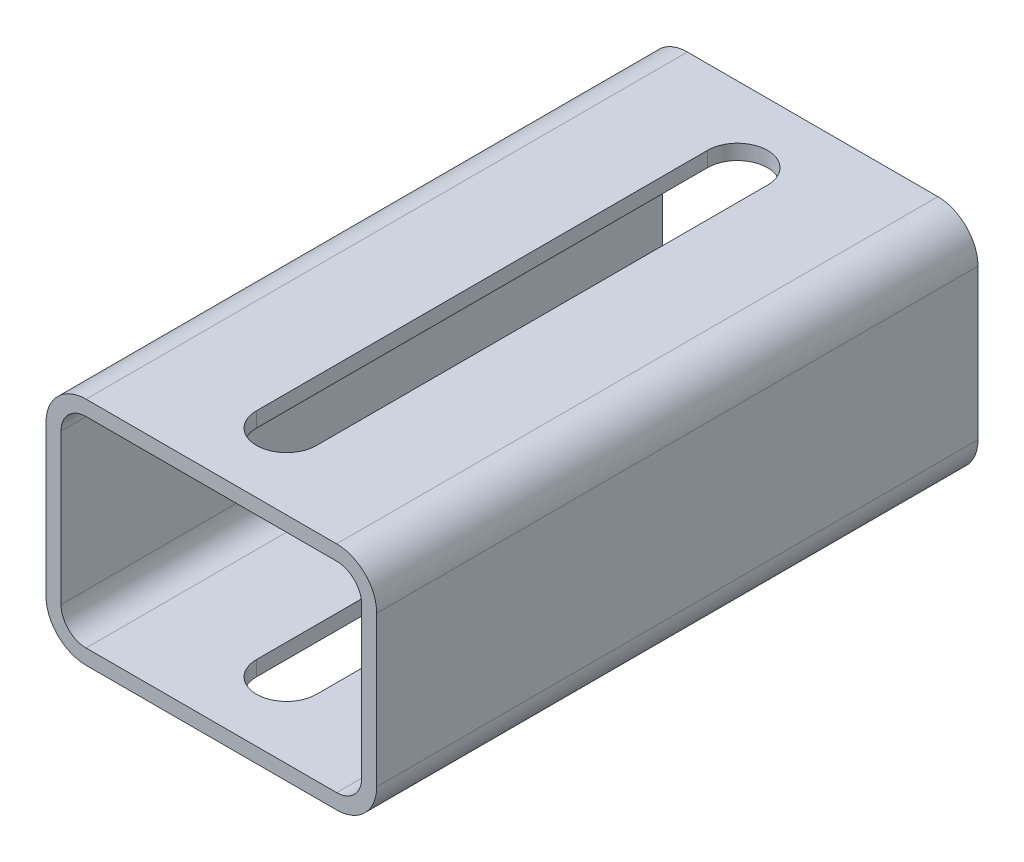
SolidWorks part; units mm, degrees
ref_plane "Front Plane" through (0, 0, 0) normal (0, 0, 1) x (1, 0, 0)
ref_plane "Top Plane" through (0, 0, 0) normal (0, 1, 0) x (1, 0, 0)
ref_plane "Right Plane" through (0, 0, 0) normal (1, 0, 0) x (0, 0, -1)
sketch "Sketch2" plane through (0, 0, 0) normal (0, 0, 1) x (1, 0, 0)
  line L1 (-25, 20) -> (25, 20)
  line L2 (-30, 15) -> (-30, -15)
  line L3 (-25, -20) -> (25, -20)
  line L4 (30, 15) -> (30, -15)
  line L5 (-30, 20) -> (30, -20) construction
  line L6 (-30, -20) -> (30, 20) construction
  arc A0 (-25, 20) -> (-30, 15) centre (-25, 15) ccw
  arc A1 (-30, -15) -> (-25, -20) centre (-25, -15) ccw
  arc A2 (25, -20) -> (30, -15) centre (25, -15) ccw
  arc A3 (25, 20) -> (30, 15) centre (25, 15) cw
  point P0 (0, 0)
  dimension "D3" = 5
  dimension "D1" = 60
  dimension "D2" = 40
extrude "Extrude-Thin1" add sketch "Sketch2" along normal mid plane 120 thin thin type one direction wall 3
sketch "Sketch4" plane through (0, 23, 0) normal (0, 1, 0) x (1, 0, 0)
  line L0 (0, 45) -> (0, -45) construction
  line L1 (6, 45) -> (6, -45)
  line L2 (-6, 45) -> (-6, -45)
  arc A0 (6, 45) -> (-6, 45) centre (0, 45) ccw
  arc A1 (-6, -45) -> (6, -45) centre (0, -45) ccw
  point P2 (0, 0)
  dimension "D2" = 6
  dimension "D1" = 90
extrude "Cut-Extrude1" cut sketch "Sketch4" against normal through all
